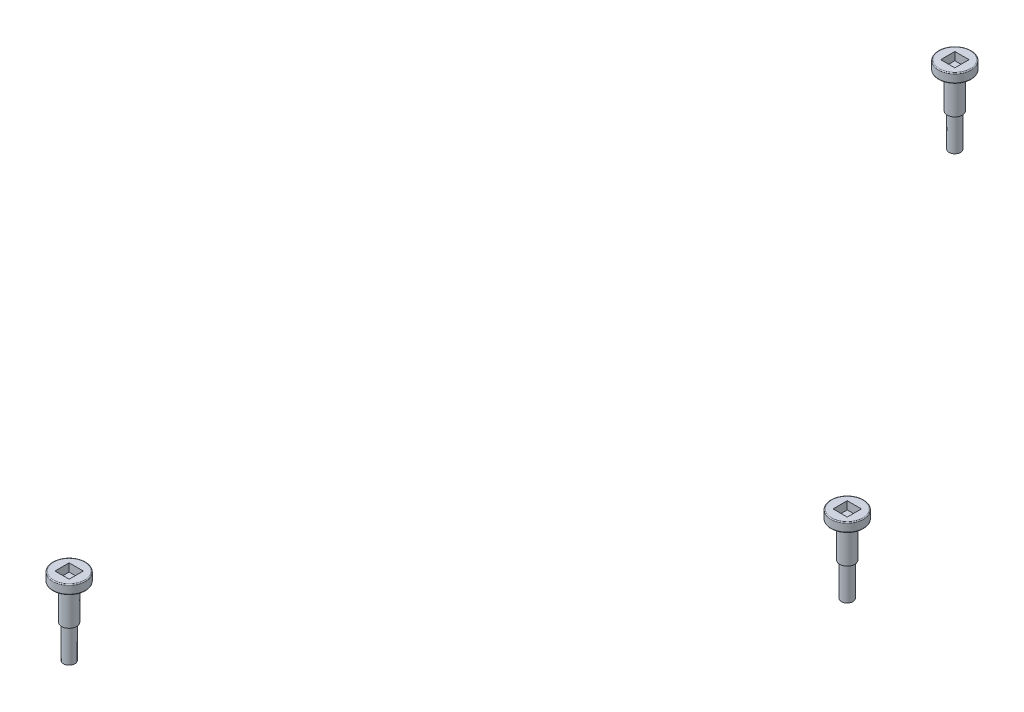
SolidWorks part; units mm, degrees
ref_plane "Front Plane" through (0, 0, 0) normal (0, 0, 1) x (1, 0, 0)
ref_plane "Top Plane" through (0, 0, 0) normal (0, 1, 0) x (1, 0, 0)
ref_plane "Right Plane" through (0, 0, 0) normal (1, 0, 0) x (0, 0, -1)
sketch "Sketch1" plane through (0, 0, 0) normal (0, 1, 0) x (1, 0, 0)
  circle A0 centre (0, 0) radius 4.699
  circle A1 centre (-96.139, 127) radius 4.699
  circle A2 centre (-96.139, -127) radius 4.699
  dimension "D5" = 9.398
  dimension "D6" = 9.398
  dimension "D7" = 9.398
  dimension "D1" = 254
  dimension "D2" = 96.139
  dimension "D3" = 96.139
  dimension "D4" = 127
extrude "Boss-Extrude1" add sketch "Sketch1" against normal blind 2.667
sketch "Sketch2" plane through (0, 0, 0) normal (0, 1, 0) x (1, 0, 0)
  circle A0 centre (-96.139, 127) radius 2.159
  circle A1 centre (0, 0) radius 2.159
  circle A2 centre (-96.139, -127) radius 2.159
  dimension "D1" = 4.318
  dimension "D2" = 4.318
  dimension "D3" = 4.318
extrude "Boss-Extrude2" add sketch "Sketch2" against normal blind 12.7
sketch "Sketch3" plane through (0, 0, 0) normal (0, 1, 0) x (1, 0, 0)
  circle A0 centre (-96.139, 127) radius 1.651
  circle A1 centre (0, 0) radius 1.651
  circle A2 centre (-96.139, -127) radius 1.651
  dimension "D1" = 3.302
  dimension "D2" = 3.302
  dimension "D3" = 3.302
extrude "Boss-Extrude3" add sketch "Sketch3" against normal blind 22.225
sketch "Sketch4" plane through (0, 0, 0) normal (0, 1, 0) x (1, 0, 0)
  line L1 (-98.171, 129.032) -> (-94.107, 129.032)
  line L2 (-98.171, 129.032) -> (-98.171, 124.968)
  line L3 (-98.171, 124.968) -> (-94.107, 124.968)
  line L4 (-94.107, 129.032) -> (-94.107, 124.968)
  line L5 (-2.032, 2.032) -> (2.032, 2.032)
  line L6 (-2.032, 2.032) -> (-2.032, -2.032)
  line L7 (-2.032, -2.032) -> (2.032, -2.032)
  line L8 (2.032, 2.032) -> (2.032, -2.032)
  line L9 (-98.171, -124.968) -> (-94.107, -124.968)
  line L10 (-98.171, -124.968) -> (-98.171, -129.032)
  line L11 (-98.171, -129.032) -> (-94.107, -129.032)
  line L12 (-94.107, -124.968) -> (-94.107, -129.032)
  circle A0 centre (-96.139, 127) radius 4.699 construction
  circle A1 centre (-96.139, -127) radius 4.699 construction
  dimension "D1" = 4.064
  dimension "D2" = 4.064
  dimension "D3" = 2.032
  dimension "D4" = 2.032
  dimension "D5" = 4.064
  dimension "D6" = 4.064
  dimension "D7" = 2.032
  dimension "D8" = 2.032
  dimension "D9" = 4.064
  dimension "D10" = 4.064
  dimension "D11" = 2.032
  dimension "D12" = 2.032
extrude "Cut-Extrude1" cut sketch "Sketch4" against normal blind 2.286
fillet "Fillet1" radius 0.254 2 edges at (-96.139, 0, 131.699) (-96.139, -2.667, 131.699)
fillet "Fillet2" radius 0.254 2 edges at (0, -2.667, 4.699) (0, 0, 4.699)
fillet "Fillet3" radius 0.254 2 edges at (-96.139, 0, -122.301) (-96.139, -2.667, -122.301)
